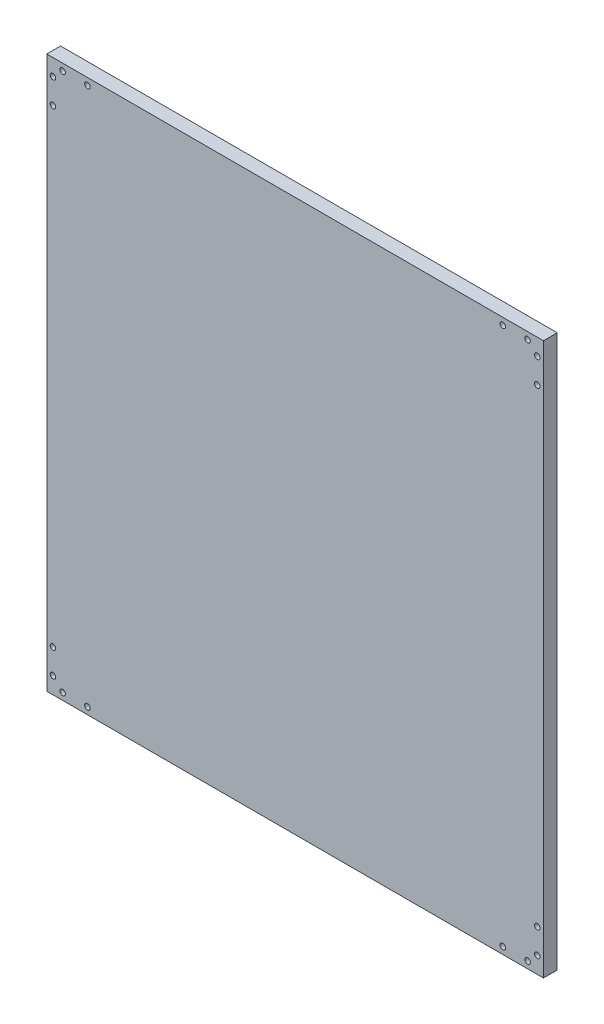
SolidWorks part; units mm, degrees
ref_plane "Спереди" through (0, 0, 0) normal (0, 0, 1) x (1, 0, 0)
ref_plane "Сверху" through (0, 0, 0) normal (0, 1, 0) x (1, 0, 0)
ref_plane "Справа" through (0, 0, 0) normal (1, 0, 0) x (0, 0, -1)
sketch "Эскиз1" plane through (0, 0, 0) normal (0, 0, 1) x (1, 0, 0)
  line L0 (0, 200) -> (0, 0) construction
  line L1 (-180, -200) -> (180, -200)
  line L2 (-180, -200) -> (-180, 200)
  line L3 (-180, 200) -> (180, 200)
  line L4 (180, -200) -> (180, 200)
  line L5 (-180, -200) -> (180, 200) construction
  line L6 (-180, 200) -> (180, -200) construction
  line L7 (0, 0) -> (-180, 0) construction
  point P0 (0, 0)
  line B0 (150.5, 195) -> (175.5, 195) construction
  line B1 (175.5, 195) -> (175.5, 170) construction
  circle B2 centre (150.5, 195) radius 2
  circle B3 centre (168.5, 195) radius 2
  circle B4 centre (175.5, 170) radius 2
  circle B5 centre (175.5, 188) radius 2
  circle B6 centre (-150.5, 195) radius 2
  circle B7 centre (-168.5, 195) radius 2
  circle B8 centre (-175.5, 170) radius 2
  circle B9 centre (-175.5, 188) radius 2
  circle B10 centre (-150.5, -195) radius 2
  circle B11 centre (-168.5, -195) radius 2
  circle B12 centre (-175.5, -170) radius 2
  circle B13 centre (-175.5, -188) radius 2
  circle B14 centre (150.5, -195) radius 2
  circle B15 centre (168.5, -195) radius 2
  circle B16 centre (175.5, -170) radius 2
  circle B17 centre (175.5, -188) radius 2
  dimension "D1" = 360
  dimension "D2" = 400
  dimension "D3" = 5
sketch_block_instance "Блок1-3"
sketch_block "Блок1" parameters "D1"=25, "D2"=25, "D3"=18, "18"=18
sketch_block_instance "Блок1-4"
sketch_block_instance "Блок1-5"
sketch_block_instance "Блок1-6"
extrude "Бобышка-Вытянуть1" add sketch "Эскиз1" along normal blind 10
